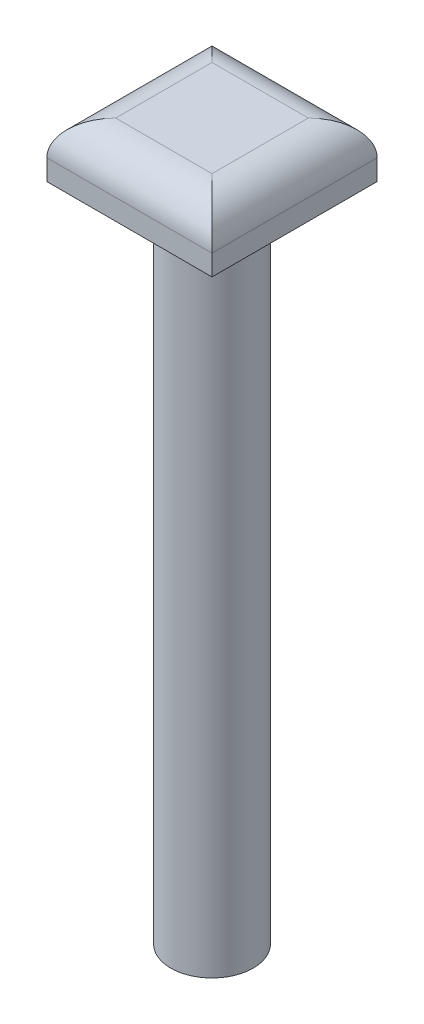
SolidWorks part; units mm, degrees
ref_plane "Front Plane" through (0, 0, 0) normal (0, 0, 1) x (1, 0, 0)
ref_plane "Top Plane" through (0, 0, 0) normal (0, 1, 0) x (1, 0, 0)
ref_plane "Right Plane" through (0, 0, 0) normal (1, 0, 0) x (0, 0, -1)
sketch "Sketch1" plane through (0, 0, 0) normal (0, 0, 1) x (1, 0, 0)
  line L0 (0, 53.2923) -> (0, -52.8) construction
  line L1 (-73.7231, 0) -> (97.8462, 0) construction
  line L2 (0, 56) -> (-12, 56)
  line L3 (-12, 56) -> (-12, 48)
  line L4 (-12, 48) -> (-6, 48)
  line L5 (-6, 48) -> (-6, -48)
  line L6 (-6, -48) -> (0, -48)
  line L7 (0, -48) -> (0, 56)
  point P7 (-9, 48)
  dimension "D1" = 96
  dimension "D2" = 48
  dimension "D3" = 12
  dimension "D4" = 6
  dimension "D5" = 8
revolve "Revolve1" add sketch "Sketch1" angle 360 about L7
sketch "Sketch3" plane through (0, 48, 0) normal (0, -1, 0) x (1, 0, 0)
  line L1 (12, 12) -> (-12, 12)
  line L2 (12, 12) -> (12, -12)
  line L3 (12, -12) -> (-12, -12)
  line L4 (-12, 12) -> (-12, -12)
  line L5 (12, 12) -> (-12, -12) construction
  line L6 (12, -12) -> (-12, 12) construction
  point P0 (0, 0)
  dimension "D1" = 24
  dimension "D2" = 24
extrude "Boss-Extrude1" add sketch "Sketch3" against normal blind 8
fillet "Fillet1" radius 5 4 edges at (-12, 56, 0) (0, 56, -12) (12, 56, 0) (0, 56, 12)
